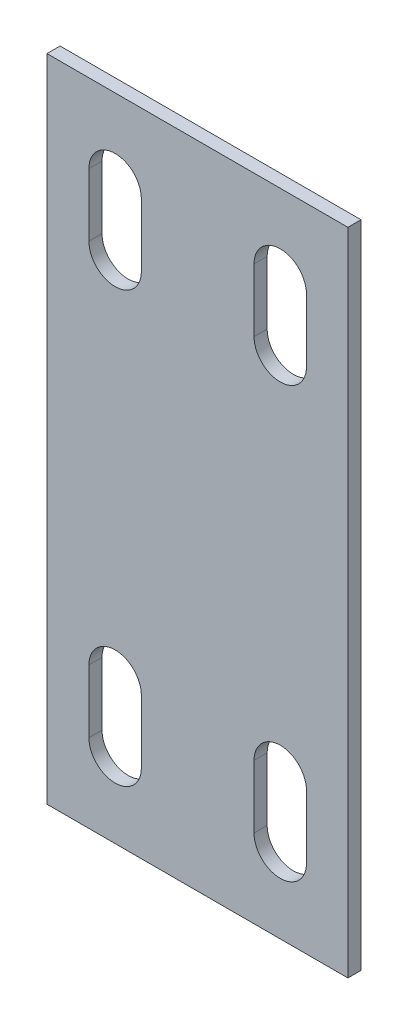
SolidWorks part; units mm, degrees
ref_plane "Front Plane" through (0, 0, 0) normal (0, 0, 1) x (1, 0, 0)
ref_plane "Top Plane" through (0, 0, 0) normal (0, 1, 0) x (1, 0, 0)
ref_plane "Right Plane" through (0, 0, 0) normal (1, 0, 0) x (0, 0, -1)
sketch "Flat Plate" plane through (0, 0, 0) normal (0, 0, 1) x (1, 0, 0)
  line L1 (-101.3811, 81.3749) -> (-28.4831, 81.3749)
  line L2 (-101.3811, 81.3749) -> (-101.3811, -76.1051)
  line L3 (-101.3811, -76.1051) -> (-28.4831, -76.1051)
  line L4 (-28.4831, 81.3749) -> (-28.4831, -76.1051)
  dimension "D1" = 72.898
  dimension "D2" = 157.48
extrude "Castor Plate" add sketch "Flat Plate" along normal blind 3.175
sketch "Holes" plane through (0, 0, 3.175) normal (0, 0, 1) x (1, 0, 0)
  line L0 (-84.8711, 47.0849) -> (-84.8711, 62.3249) construction
  line L1 (-91.2211, 47.0849) -> (-91.2211, 62.3249)
  line L2 (-78.5211, 47.0849) -> (-78.5211, 62.3249)
  line L3 (-44.8712, -57.0551) -> (-44.8712, -41.8151) construction
  line L4 (-51.2212, -57.0551) -> (-51.2212, -41.8151)
  line L5 (-38.5212, -57.0551) -> (-38.5212, -41.8151)
  line L6 (-84.8711, -41.8151) -> (-84.8711, -57.0551) construction
  line L7 (-78.5211, -41.8151) -> (-78.5211, -57.0551)
  line L8 (-91.2211, -41.8151) -> (-91.2211, -57.0551)
  line L9 (-44.8712, 62.3249) -> (-44.8712, 47.0849) construction
  line L10 (-38.5212, 62.3249) -> (-38.5212, 47.0849)
  line L11 (-51.2212, 62.3249) -> (-51.2212, 47.0849)
  line L12 (-101.3811, 81.3749) -> (-101.3811, -76.1051) construction
  line L13 (-28.4831, 81.3749) -> (-101.3811, 81.3749) construction
  arc A0 (-91.2211, 47.0849) -> (-78.5211, 47.0849) centre (-84.8711, 47.0849) ccw
  arc A1 (-78.5211, 62.3249) -> (-91.2211, 62.3249) centre (-84.8711, 62.3249) ccw
  arc A2 (-51.2212, -57.0551) -> (-38.5212, -57.0551) centre (-44.8712, -57.0551) ccw
  arc A3 (-38.5212, -41.8151) -> (-51.2212, -41.8151) centre (-44.8712, -41.8151) ccw
  arc A4 (-78.5211, -41.8151) -> (-91.2211, -41.8151) centre (-84.8711, -41.8151) ccw
  arc A5 (-91.2211, -57.0551) -> (-78.5211, -57.0551) centre (-84.8711, -57.0551) ccw
  arc A6 (-38.5212, 62.3249) -> (-51.2212, 62.3249) centre (-44.8712, 62.3249) ccw
  arc A7 (-51.2212, 47.0849) -> (-38.5212, 47.0849) centre (-44.8712, 47.0849) ccw
  point P2 (-84.8711, 54.7049)
  point P9 (-44.8712, -49.4351)
  point P16 (-84.8711, -49.4351)
  point P23 (-44.8712, 54.7049)
  point P30 (-84.8711, -63.4051)
  point P31 (-44.8712, -63.4051)
  point P32 (-84.8711, 68.6749)
  point P33 (-44.8712, 68.6749)
  point P34 (-84.8711, -35.4651)
  point P35 (-84.8711, 40.7349)
  point P36 (-46.2455, 18.6522)
  dimension "D1" = 39.9999
  dimension "D2" = 39.9999
  dimension "D3" = 76.2
  dimension "D4" = 12.7
  dimension "D5" = 15.24
  dimension "D6" = 10.16
extrude "Cut-Extrude1" cut sketch "Holes" against normal blind 3.175
